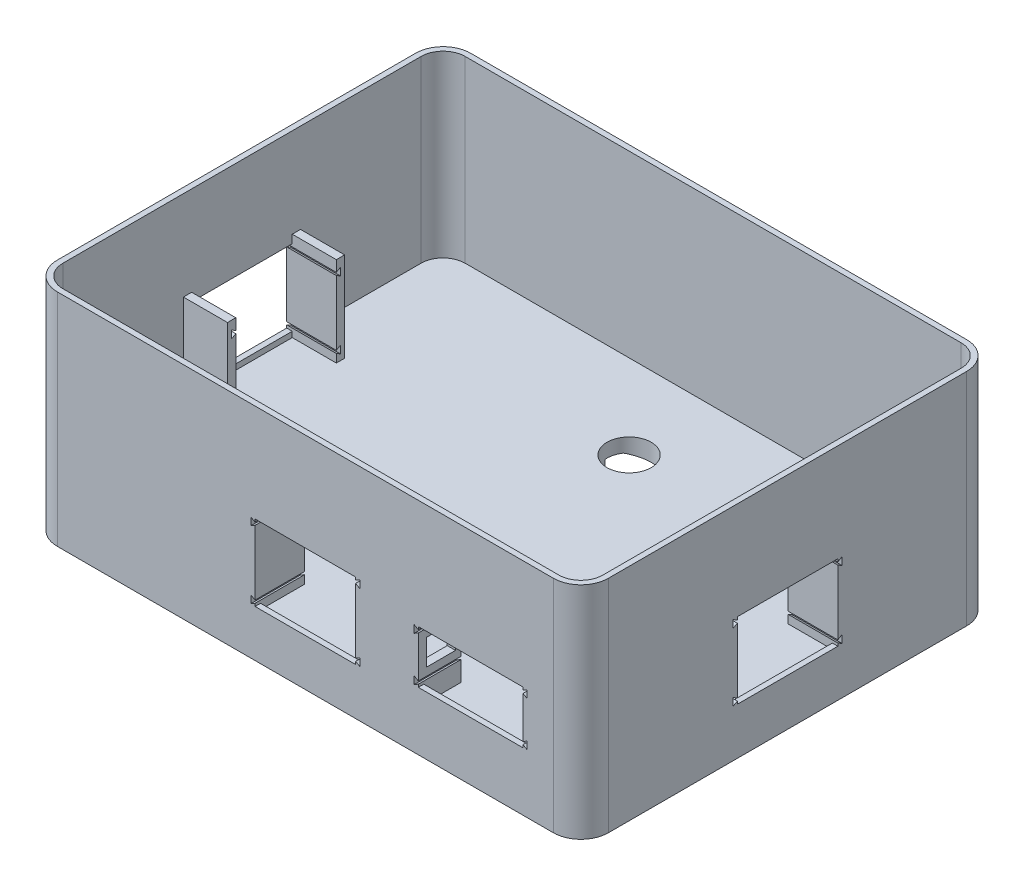
SolidWorks part; units mm, degrees
ref_plane "Front Plane" through (0, 0, 0) normal (0, 0, 1) x (1, 0, 0)
ref_plane "Top Plane" through (0, 0, 0) normal (0, 1, 0) x (1, 0, 0)
ref_plane "Right Plane" through (0, 0, 0) normal (1, 0, 0) x (0, 0, -1)
sketch "Sketch2" plane through (0, 0, 0) normal (0, 1, 0) x (1, 0, 0)
  line L1 (-100, 75) -> (100, 75)
  line L2 (-100, 75) -> (-100, -75)
  line L3 (-100, -75) -> (100, -75)
  line L4 (100, 75) -> (100, -75)
  line L5 (-100, 75) -> (100, -75) construction
  line L6 (-100, -75) -> (100, 75) construction
  point P0 (0, 0)
  dimension "D1" = 200
  dimension "D2" = 150
extrude "Boss-Extrude1" add sketch "Sketch2" along normal blind 80
fillet "Fillet1" radius 10 4 edges at (-100, 40, -75) (100, 40, -75) (100, 40, 75) (-100, 40, 75)
shell "Shell1" thickness 2
sketch "Sketch5" plane through (0, 0, 75) normal (0, 0, 1) x (1, 0, 0)
  line L1 (-18.25, 44.5) -> (18.25, 44.5)
  line L2 (-18.25, 44.5) -> (-18.25, 17)
  line L3 (-18.25, 17) -> (18.25, 17)
  line L4 (18.25, 44.5) -> (18.25, 17)
  line L5 (-18.25, 43.5) -> (-19.75, 44.366)
  line L6 (-19.75, 44.366) -> (-19.75, 41.634)
  line L7 (-19.75, 41.634) -> (-18.25, 42.5)
  line L8 (-18.25, 42.5) -> (-18.25, 43.5)
  line L9 (0, 44.5) -> (0, 17) construction
  line L10 (-18.25, 30.75) -> (18.25, 30.75) construction
  line L11 (-19.75, 19.866) -> (-18.25, 19)
  line L12 (-19.75, 17.134) -> (-19.75, 19.866)
  line L13 (-18.25, 18) -> (-19.75, 17.134)
  line L14 (-18.25, 19) -> (-18.25, 18)
  line L15 (19.75, 17.134) -> (19.75, 19.866)
  line L16 (18.25, 18) -> (19.75, 17.134)
  line L17 (18.25, 19) -> (18.25, 18)
  line L18 (19.75, 19.866) -> (18.25, 19)
  line L19 (19.75, 41.634) -> (18.25, 42.5)
  line L20 (19.75, 44.366) -> (19.75, 41.634)
  line L21 (18.25, 43.5) -> (19.75, 44.366)
  line L22 (18.25, 42.5) -> (18.25, 43.5)
  line L23 (-90, 15) -> (90, 15) construction
  point P4 (0, 17)
  dimension "D1" = 36.5
  dimension "D2" = 27.5
  dimension "D3" = 60
  dimension "D4" = 60
  dimension "D5" = 1
  dimension "D6" = 1
  dimension "D7" = 1.5
  dimension "D8" = 2
extrude "Cut-Extrude1" cut sketch "Sketch5" against normal up to surface (2 mm away) contours L1 L4 L3 L2 | L7 L8 L5 L6 | L12 L11 L14 L13 | L20 L19 L22 L21 | L15 L18 L17 L16 up to face at (0, 47.5, 73)
sketch "Sketch6" plane through (0, 0, 73) normal (0, 0, -1) x (-1, 0, 0)
  line L0 (18.25, 15) -> (21.25, 15)
  line L2 (-21.25, 47.5) -> (-21.25, 15)
  line L4 (19.75, 44.366) -> (18.25, 43.5)
  line L5 (19.75, 41.634) -> (19.75, 44.366)
  line L6 (18.25, 42.5) -> (19.75, 41.634)
  line L7 (18.25, 43.5) -> (18.25, 42.5)
  line L8 (19.75, 44.366) -> (18.25, 43.5)
  line L9 (19.75, 41.634) -> (19.75, 44.366)
  line L10 (18.25, 42.5) -> (19.75, 41.634)
  line L12 (18.25, 44.5) -> (-18.25, 44.5)
  line L13 (-18.25, 44.5) -> (-18.25, 17)
  line L14 (-18.25, 17) -> (18.25, 17)
  line L15 (18.25, 17) -> (18.25, 44.5)
  line L17 (-18.25, 47.5) -> (-18.25, 43.5)
  line L19 (18.25, 15) -> (18.25, 18)
  line L20 (-19.75, 41.634) -> (-18.25, 42.5)
  line L21 (-18.25, 42.5) -> (-18.25, 43.5)
  line L22 (-18.25, 43.5) -> (-19.75, 44.366)
  line L23 (-19.75, 44.366) -> (-19.75, 41.634)
  line L24 (-19.75, 41.634) -> (-18.25, 42.5)
  line L26 (-18.25, 43.5) -> (-19.75, 44.366)
  line L27 (-19.75, 44.366) -> (-19.75, 41.634)
  line L28 (-19.75, 19.866) -> (-19.75, 17.134)
  line L29 (-18.25, 19) -> (-19.75, 19.866)
  line L30 (-18.25, 18) -> (-18.25, 19)
  line L31 (-19.75, 17.134) -> (-18.25, 18)
  line L32 (-19.75, 19.866) -> (-19.75, 17.134)
  line L33 (-18.25, 19) -> (-19.75, 19.866)
  line L35 (-19.75, 17.134) -> (-18.25, 18)
  line L36 (19.75, 19.866) -> (18.25, 19)
  line L37 (18.25, 19) -> (18.25, 18)
  line L38 (18.25, 18) -> (19.75, 17.134)
  line L39 (19.75, 17.134) -> (19.75, 19.866)
  line L40 (19.75, 19.866) -> (18.25, 19)
  line L42 (18.25, 18) -> (19.75, 17.134)
  line L43 (19.75, 17.134) -> (19.75, 19.866)
  line L44 (21.25, 47.5) -> (21.25, 15)
  line L45 (-18.25, 15) -> (-21.25, 15)
  line L46 (-18.25, 42.5) -> (-18.25, 19)
  line L47 (18.25, 43.5) -> (18.25, 47.5)
  line L48 (18.25, 19) -> (18.25, 42.5)
  line L49 (-18.25, 18) -> (-18.25, 15)
  line L50 (21.25, 47.5) -> (18.25, 47.5)
  line L51 (-21.25, 47.5) -> (-18.25, 47.5)
  line L54 (18.25, 44.5) -> (-18.25, 44.5) construction
  line L55 (90, 15) -> (-90, 15) construction
  dimension "D6" = 3
  dimension "D7" = 3
  dimension "D8" = 3
  dimension "D1" = 0
  dimension "D2" = 0
  dimension "D3" = 0
  dimension "D4" = 0
  dimension "D5" = 0
extrude "Boss-Extrude2" add sketch "Sketch6" along normal blind 16
sketch "Sketch7" plane through (100, 0, 0) normal (1, 0, 0) x (0, 0, -1)
  line L0 (-65, 15) -> (65, 15) construction
  line L1 (-18.25, 44.5) -> (18.25, 44.5)
  line L2 (-18.25, 44.5) -> (-18.25, 17)
  line L3 (-18.25, 17) -> (18.25, 17)
  line L4 (18.25, 44.5) -> (18.25, 17)
  line L5 (-18.25, 43.5) -> (-19.75, 44.366)
  line L6 (-19.75, 44.366) -> (-19.75, 41.634)
  line L7 (-19.75, 41.634) -> (-18.25, 42.5)
  line L8 (-18.25, 42.5) -> (-18.25, 43.5)
  line L9 (0, 44.5) -> (0, 17) construction
  line L10 (-18.25, 30.75) -> (18.25, 30.75) construction
  line L11 (-19.75, 19.866) -> (-18.25, 19)
  line L12 (-19.75, 17.134) -> (-19.75, 19.866)
  line L13 (-18.25, 18) -> (-19.75, 17.134)
  line L14 (-18.25, 19) -> (-18.25, 18)
  line L15 (19.75, 17.134) -> (19.75, 19.866)
  line L16 (18.25, 18) -> (19.75, 17.134)
  line L17 (18.25, 19) -> (18.25, 18)
  line L18 (19.75, 19.866) -> (18.25, 19)
  line L19 (19.75, 41.634) -> (18.25, 42.5)
  line L20 (19.75, 44.366) -> (19.75, 41.634)
  line L21 (18.25, 43.5) -> (19.75, 44.366)
  line L22 (18.25, 42.5) -> (18.25, 43.5)
  dimension "D1" = 36.5
  dimension "D2" = 27.5
  dimension "D3" = 60
  dimension "D4" = 60
  dimension "D5" = 1
  dimension "D6" = 1
  dimension "D7" = 1.5
  dimension "D8" = 2
extrude "Cut-Extrude2" cut sketch "Sketch7" against normal blind 2 contours L1 L4 L3 L2 | L7 L8 L5 L6 | L12 L11 L14 L13 | L20 L19 L22 L21 | L15 L18 L17 L16
sketch "Sketch8" plane through (98, 0, 0) normal (-1, 0, 0) x (0, 0, 1)
  line L0 (65, 15) -> (-65, 15) construction
  line L1 (-21.25, 47.5) -> (-18.25, 47.5)
  line L2 (-21.25, 47.5) -> (-21.25, 15)
  line L3 (-21.25, 15) -> (-18.25, 15)
  line L4 (19.75, 44.366) -> (18.25, 43.5)
  line L5 (19.75, 41.634) -> (19.75, 44.366)
  line L6 (18.25, 42.5) -> (19.75, 41.634)
  line L7 (18.25, 43.5) -> (18.25, 42.5)
  line L8 (19.75, 44.366) -> (18.25, 43.5)
  line L9 (19.75, 41.634) -> (19.75, 44.366)
  line L10 (18.25, 42.5) -> (19.75, 41.634)
  line L20 (-19.75, 41.634) -> (-18.25, 42.5)
  line L21 (-18.25, 42.5) -> (-18.25, 43.5)
  line L22 (-18.25, 43.5) -> (-19.75, 44.366)
  line L23 (-19.75, 44.366) -> (-19.75, 41.634)
  line L24 (-19.75, 41.634) -> (-18.25, 42.5)
  line L26 (-18.25, 43.5) -> (-19.75, 44.366)
  line L27 (-19.75, 44.366) -> (-19.75, 41.634)
  line L28 (-19.75, 19.866) -> (-19.75, 17.134)
  line L29 (-18.25, 19) -> (-19.75, 19.866)
  line L30 (-18.25, 18) -> (-18.25, 19)
  line L31 (-19.75, 17.134) -> (-18.25, 18)
  line L32 (-19.75, 19.866) -> (-19.75, 17.134)
  line L33 (-18.25, 19) -> (-19.75, 19.866)
  line L35 (-19.75, 17.134) -> (-18.25, 18)
  line L36 (19.75, 19.866) -> (18.25, 19)
  line L37 (18.25, 19) -> (18.25, 18)
  line L38 (18.25, 18) -> (19.75, 17.134)
  line L39 (19.75, 17.134) -> (19.75, 19.866)
  line L40 (19.75, 19.866) -> (18.25, 19)
  line L42 (18.25, 18) -> (19.75, 17.134)
  line L43 (19.75, 17.134) -> (19.75, 19.866)
  line L44 (-18.25, 47.5) -> (-18.25, 43.5)
  line L46 (-18.25, 42.5) -> (-18.25, 19) construction
  line L47 (18.25, 44.5) -> (-18.25, 44.5) construction
  line L48 (-18.25, 42.5) -> (-18.25, 19)
  line L49 (-18.25, 18) -> (-18.25, 15)
  line L50 (18.25, 42.5) -> (18.25, 19) construction
  line L51 (18.25, 47.5) -> (21.25, 47.5)
  line L52 (18.25, 47.5) -> (18.25, 43.5)
  line L53 (18.25, 15) -> (21.25, 15)
  line L54 (21.25, 47.5) -> (21.25, 15)
  line L55 (18.25, 42.5) -> (18.25, 19)
  line L56 (18.25, 18) -> (18.25, 15)
  dimension "D6" = 3
  dimension "D7" = 3
  dimension "D2" = 3
  dimension "D1" = 0
  dimension "D3" = 0
  dimension "D4" = 0
  dimension "D5" = 0
extrude "Boss-Extrude3" add sketch "Sketch8" along normal blind 16
sketch "Sketch10" plane through (-100, 0, 0) normal (-1, 0, 0) x (0, 0, 1)
  line L1 (-18.25, 44.5) -> (18.25, 44.5)
  line L2 (-18.25, 44.5) -> (-18.25, 17)
  line L3 (-18.25, 17) -> (18.25, 17)
  line L4 (18.25, 44.5) -> (18.25, 17)
  line L5 (-18.25, 43.5) -> (-19.75, 44.366)
  line L6 (-19.75, 44.366) -> (-19.75, 41.634)
  line L7 (-19.75, 41.634) -> (-18.25, 42.5)
  line L8 (-18.25, 42.5) -> (-18.25, 43.5)
  line L9 (0, 44.5) -> (0, 17) construction
  line L10 (-18.25, 30.75) -> (18.25, 30.75) construction
  line L11 (-19.75, 19.866) -> (-18.25, 19)
  line L12 (-19.75, 17.134) -> (-19.75, 19.866)
  line L13 (-18.25, 18) -> (-19.75, 17.134)
  line L14 (-18.25, 19) -> (-18.25, 18)
  line L15 (19.75, 17.134) -> (19.75, 19.866)
  line L16 (18.25, 18) -> (19.75, 17.134)
  line L17 (18.25, 19) -> (18.25, 18)
  line L18 (19.75, 19.866) -> (18.25, 19)
  line L19 (19.75, 41.634) -> (18.25, 42.5)
  line L20 (19.75, 44.366) -> (19.75, 41.634)
  line L21 (18.25, 43.5) -> (19.75, 44.366)
  line L22 (18.25, 42.5) -> (18.25, 43.5)
  line L23 (-65, 15) -> (65, 15) construction
  dimension "D1" = 36.5
  dimension "D2" = 27.5
  dimension "D3" = 60
  dimension "D4" = 60
  dimension "D5" = 1
  dimension "D6" = 1
  dimension "D7" = 1.5
  dimension "D8" = 2
extrude "Cut-Extrude4" cut sketch "Sketch10" against normal blind 2 contours L1 L4 L3 L2 | L7 L8 L5 L6 | L12 L11 L14 L13 | L20 L19 L22 L21 | L15 L18 L17 L16
sketch "Sketch11" plane through (-98, 0, 0) normal (1, 0, 0) x (0, 0, -1)
  line L1 (-18.25, 42.5) -> (-18.25, 19) construction
  line L2 (-18.25, 47.5) -> (-21.25, 47.5)
  line L3 (-18.25, 47.5) -> (-18.25, 43.5)
  line L4 (19.75, 44.366) -> (18.25, 43.5)
  line L5 (19.75, 41.634) -> (19.75, 44.366)
  line L6 (18.25, 42.5) -> (19.75, 41.634)
  line L7 (18.25, 43.5) -> (18.25, 42.5)
  line L8 (19.75, 44.366) -> (18.25, 43.5)
  line L9 (19.75, 41.634) -> (19.75, 44.366)
  line L10 (18.25, 42.5) -> (19.75, 41.634)
  line L20 (-19.75, 41.634) -> (-18.25, 42.5)
  line L21 (-18.25, 42.5) -> (-18.25, 43.5)
  line L22 (-18.25, 43.5) -> (-19.75, 44.366)
  line L23 (-19.75, 44.366) -> (-19.75, 41.634)
  line L24 (-19.75, 41.634) -> (-18.25, 42.5)
  line L26 (-18.25, 43.5) -> (-19.75, 44.366)
  line L27 (-19.75, 44.366) -> (-19.75, 41.634)
  line L28 (-19.75, 19.866) -> (-19.75, 17.134)
  line L29 (-18.25, 19) -> (-19.75, 19.866)
  line L30 (-18.25, 18) -> (-18.25, 19)
  line L31 (-19.75, 17.134) -> (-18.25, 18)
  line L32 (-19.75, 19.866) -> (-19.75, 17.134)
  line L33 (-18.25, 19) -> (-19.75, 19.866)
  line L35 (-19.75, 17.134) -> (-18.25, 18)
  line L36 (19.75, 19.866) -> (18.25, 19)
  line L37 (18.25, 19) -> (18.25, 18)
  line L38 (18.25, 18) -> (19.75, 17.134)
  line L39 (19.75, 17.134) -> (19.75, 19.866)
  line L40 (19.75, 19.866) -> (18.25, 19)
  line L42 (18.25, 18) -> (19.75, 17.134)
  line L43 (19.75, 17.134) -> (19.75, 19.866)
  line L44 (-18.25, 15) -> (-21.25, 15)
  line L45 (-21.25, 47.5) -> (-21.25, 15)
  line L46 (65, 15) -> (-65, 15) construction
  line L47 (18.25, 44.5) -> (-18.25, 44.5) construction
  line L48 (-18.25, 42.5) -> (-18.25, 19)
  line L49 (-18.25, 18) -> (-18.25, 15)
  line L50 (18.25, 42.5) -> (18.25, 19) construction
  line L51 (18.25, 47.5) -> (21.25, 47.5)
  line L52 (18.25, 47.5) -> (18.25, 43.5)
  line L53 (18.25, 15) -> (21.25, 15)
  line L54 (21.25, 47.5) -> (21.25, 15)
  line L55 (18.25, 42.5) -> (18.25, 19)
  line L56 (18.25, 18) -> (18.25, 15)
  dimension "D2" = 3
  dimension "D6" = 3
  dimension "D7" = 3
  dimension "D1" = 0
  dimension "D3" = 0
  dimension "D4" = 0
  dimension "D5" = 0
extrude "Boss-Extrude4" add sketch "Sketch11" along normal blind 16
sketch "Sketch13" plane through (0, 0, 75) normal (0, 0, 1) x (1, 0, 0)
  line L0 (-18.25, 30.75) -> (18.25, 30.75) construction
  line L1 (-18.25, 30.75) -> (18.25, 30.75) construction
  line L2 (41, 39.3) -> (39.5, 40.166)
  line L3 (41, 40.3) -> (79, 40.3)
  line L4 (41, 40.3) -> (41, 21.2)
  line L5 (41, 21.2) -> (79, 21.2)
  line L6 (79, 40.3) -> (79, 21.2)
  line L7 (39.5, 40.166) -> (39.5, 37.434)
  line L8 (39.5, 37.434) -> (41, 38.3)
  line L9 (41, 39.3) -> (41, 38.3)
  line L10 (60, 40.3) -> (60, 21.2) construction
  line L11 (41, 22.2) -> (39.5, 21.334)
  line L12 (39.5, 21.334) -> (39.5, 24.066)
  line L13 (39.5, 24.066) -> (41, 23.2)
  line L14 (41, 22.2) -> (41, 23.2)
  line L15 (79, 22.2) -> (79, 23.2)
  line L16 (80.5, 24.066) -> (79, 23.2)
  line L17 (80.5, 21.334) -> (80.5, 24.066)
  line L18 (79, 22.2) -> (80.5, 21.334)
  line L19 (79, 39.3) -> (80.5, 40.166)
  line L20 (80.5, 40.166) -> (80.5, 37.434)
  line L21 (80.5, 37.434) -> (79, 38.3)
  line L22 (79, 39.3) -> (79, 38.3)
  point P6 (41, 30.75)
  point P7 (60, 21.2)
  dimension "D1" = 19.1
  dimension "D2" = 38
  dimension "D3" = 60
  dimension "D4" = 60
  dimension "D5" = 60
  dimension "D6" = 1
  dimension "D7" = 1
  dimension "D8" = 1.5
extrude "Cut-Extrude5" cut sketch "Sketch13" against normal up to surface (2 mm away) contours L3 L6 L5 L4 | L7 L8 L9 L2 | L12 L13 L14 L11 | L17 L16 L15 L18 | L20 L21 L22 L19 up to face at (0, 41.5833, 73)
sketch "Sketch14" plane through (0, 0, 73) normal (0, 0, -1) x (-1, 0, 0)
  line L0 (-21.25, 15) -> (-90, 15) construction
  line L1 (-79, 43.3) -> (-82, 43.3)
  line L2 (-79, 43.3) -> (-79, 39.3)
  line L3 (-79, 15) -> (-82, 15)
  line L6 (-82, 43.3) -> (-82, 15)
  line L12 (-39.5, 40.166) -> (-41, 39.3)
  line L13 (-39.5, 37.434) -> (-39.5, 40.166)
  line L14 (-41, 38.3) -> (-39.5, 37.434)
  line L15 (-41, 39.3) -> (-41, 38.3)
  line L16 (-39.5, 40.166) -> (-41, 39.3)
  line L17 (-39.5, 37.434) -> (-39.5, 40.166)
  line L18 (-41, 38.3) -> (-39.5, 37.434)
  line L20 (-79, 39.3) -> (-80.5, 40.166)
  line L21 (-80.5, 40.166) -> (-80.5, 37.434)
  line L22 (-80.5, 37.434) -> (-79, 38.3)
  line L23 (-79, 38.3) -> (-79, 39.3)
  line L24 (-79, 39.3) -> (-80.5, 40.166)
  line L25 (-80.5, 40.166) -> (-80.5, 37.434)
  line L26 (-80.5, 37.434) -> (-79, 38.3)
  line L28 (-79, 22.2) -> (-79, 23.2)
  line L29 (-79, 23.2) -> (-80.5, 24.066)
  line L30 (-80.5, 24.066) -> (-80.5, 21.334)
  line L31 (-80.5, 21.334) -> (-79, 22.2)
  line L33 (-79, 23.2) -> (-80.5, 24.066)
  line L34 (-80.5, 24.066) -> (-80.5, 21.334)
  line L35 (-80.5, 21.334) -> (-79, 22.2)
  line L36 (-39.5, 21.334) -> (-39.5, 24.066)
  line L37 (-39.5, 24.066) -> (-41, 23.2)
  line L38 (-41, 23.2) -> (-41, 22.2)
  line L39 (-41, 22.2) -> (-39.5, 21.334)
  line L40 (-39.5, 21.334) -> (-39.5, 24.066)
  line L41 (-39.5, 24.066) -> (-41, 23.2)
  line L43 (-41, 22.2) -> (-39.5, 21.334)
  line L44 (-41, 40.3) -> (-79, 40.3) construction
  line L45 (-41, 43.3) -> (-38, 43.3)
  line L46 (-41, 43.3) -> (-41, 39.3)
  line L47 (-41, 15) -> (-38, 15)
  line L48 (-38, 43.3) -> (-38, 15)
  line L49 (-79, 38.3) -> (-79, 23.2) construction
  line L50 (-41, 38.3) -> (-41, 23.2) construction
  line L51 (-79, 38.3) -> (-79, 23.2)
  line L52 (-79, 22.2) -> (-79, 15)
  line L53 (-41, 38.3) -> (-41, 23.2)
  line L54 (-41, 22.2) -> (-41, 15)
  point P28 (-83.5378, 48.3)
  point P31 (-43.1444, 48.3)
  dimension "D1" = 3
  dimension "D6" = 3
  dimension "D7" = 3
  dimension "D2" = 0
  dimension "D3" = 0
  dimension "D4" = 0
  dimension "D5" = 0
extrude "Boss-Extrude5" add sketch "Sketch14" along normal blind 13.5
sketch "Sketch15" plane through (38, 0, 0) normal (-1, 0, 0) x (0, 0, 1)
  line L4 (59.5, 15) -> (59.5, 43.3) construction
  line L5 (73, 15) -> (73, 43.3) construction
  line L6 (59.5, 43.3) -> (59.5, 15) construction
  line L7 (59.5, 37.434) -> (75, 37.434) construction
  line L8 (59.5, 24.066) -> (75, 24.066) construction
  line L12 (72, 26.066) -> (72, 35.434)
  line L13 (72, 35.434) -> (61.5, 35.434)
  line L14 (61.5, 35.434) -> (61.5, 26.066)
  line L15 (61.5, 26.066) -> (72, 26.066)
  dimension "D1" = 2
  dimension "D2" = 1
  dimension "D3" = 2
  dimension "D4" = 2
extrude "Cut-Extrude6" cut sketch "Sketch15" against normal up to surface (3 mm away) up to face at (41, 30.75, 67.25)
sketch "Sketch18" plane through (0, 0, 0) normal (1, 0, 0) x (0, 0, -1)
  line L0 (0, 0) -> (0, 10) construction
  line L3 (-42.5, 0) -> (-70, 0)
  line L4 (-70, 0) -> (-47.5, 10)
  line L5 (-47.5, 10) -> (-42.5, 10)
  line L6 (-42.5, 10) -> (-42.5, 0)
  line L7 (65, 0) -> (-65, 0) construction
  dimension "D1" = 10
  dimension "D2" = 70
  dimension "D3" = 5
  dimension "D4" = 42.5
revolve "Cut-Revolve1" cut sketch "Sketch18" angle 360 about L0
sketch "Sketch20" plane through (0, 0, 0) normal (0, -1, 0) x (1, 0, 0)
  circle A0 centre (0, -42.5) radius 8
  circle A1 centre (0, 0) radius 42.5 construction
  circle A2 centre (0, 0) radius 42.5 construction
  point P2 (0, 0)
  point P4 (0, -52.2555)
  point P5 (0, -42.5)
  dimension "D1" = 16
extrude "Cut-Extrude8" cut sketch "Sketch20" against normal up to surface (15 mm away) up to face at (12, 15, 26.25)
